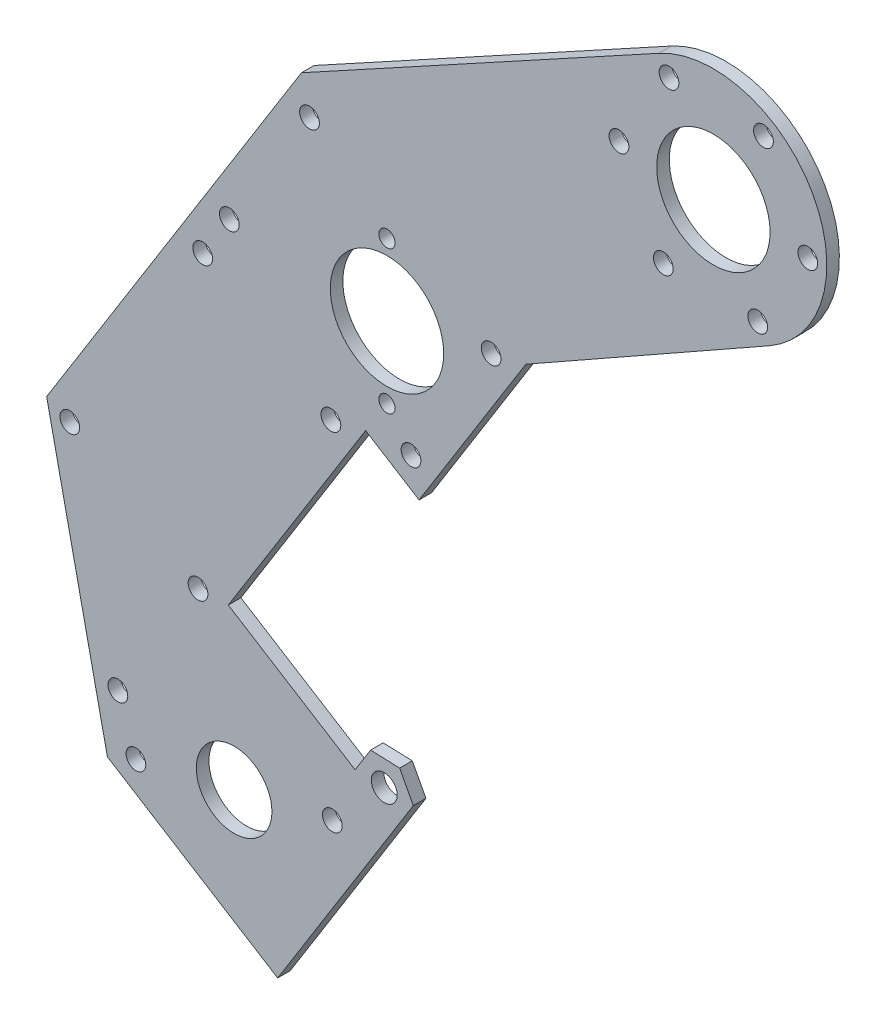
SolidWorks part; units mm, degrees
material "6061 Alloy"
ref_plane "Front Plane" through (0, 0, 0) normal (0, 0, 1) x (1, 0, 0)
ref_plane "Top Plane" through (0, 0, 0) normal (0, 1, 0) x (1, 0, 0)
ref_plane "Right Plane" through (0, 0, 0) normal (1, 0, 0) x (0, 0, -1)
sketch "Sketch1" plane through (0, 0, -14.1946) normal (0, 0, 1) x (1, 0, 0)
  line L0 (-11.4036, 461.0409) -> (18.8813, 509.5069)
  line L1 (-54.3079, 487.8505) -> (-69.6155, 558.824)
  line L2 (8.1111, 516.2368) -> (-23.8465, 536.2061)
  line L3 (18.8813, 509.5069) -> (22.7847, 515.7536)
  line L4 (-11.4036, 461.0409) -> (-54.3079, 487.8505)
  line L5 (-69.6155, 558.824) -> (-5.4017, 661.5875)
  line L6 (-23.8465, 536.2061) -> (10.7592, 591.5868)
  line L9 (12.0145, 522.4836) -> (8.1111, 516.2368)
  line L10 (51.1419, 626.2552) -> (112.462, 660.9373)
  line L11 (10.7592, 591.5868) -> (24.222, 583.1743)
  line L13 (24.222, 583.1743) -> (51.1419, 626.2552)
  line L16 (-5.4017, 661.5875) -> (84.678, 710.8773)
  line L17 (17.3996, 519.1186) -> (21.5031, 525.6857) construction
  line L18 (22.7847, 515.7536) -> (19.3423, 522.2277)
  line L19 (19.3423, 522.2277) -> (12.0145, 522.4836)
  circle A2 centre (16.1415, 618.1747) radius 14.2875
  circle A3 centre (-22.3737, 496.6228) radius 9.525
  circle A5 centre (98.3945, 685.8096) radius 14.2875
  arc A7 (112.462, 660.9373) -> (84.678, 710.8773) centre (98.3945, 685.8096) ccw
  circle A8 centre (16.1415, 618.1747) radius 127.508 construction
  circle A9 centre (15.4568, 516.0095) radius 6.35 construction
  point P12 (-22.3737, 496.6228)
  point P33 (98.3945, 685.8096)
  dimension "D1" = 120
extrude "Boss-Extrude1" add sketch "Sketch1" along normal blind 3.175
sketch "Sketch17" plane through (0, 0, -11.0196) normal (0, 0, 1) x (1, 0, 0)
  line L0 (-47.1227, 490.909) -> (-22.3737, 496.6228)
  line L1 (-22.3737, 496.6228) -> (2.3753, 502.3365)
  line L2 (16.1415, 618.1747) -> (37.6819, 604.7147) construction
  line L12 (24.222, 583.1743) -> (51.1419, 626.2552) construction
  line L13 (37.6819, 604.7147) -> (27.587, 588.5594) construction
  line L14 (27.587, 588.5594) -> (22.2019, 591.9244) construction
  line L15 (22.2019, 591.9244) -> (-28.9566, 623.8918) construction
  line L16 (-5.4017, 661.5875) -> (-69.6155, 558.824) construction
  line L17 (-28.9566, 623.8918) -> (-23.5715, 620.5268) construction
  line L18 (-23.5715, 620.5268) -> (-3.3816, 652.8374) construction
  line L19 (-3.3816, 652.8374) -> (42.3918, 624.2351) construction
  line L20 (10.7592, 591.5868) -> (5.3741, 594.9518) construction
  line L21 (5.3741, 594.9518) -> (-31.4748, 535.9811) construction
  line L22 (-31.4748, 535.9811) -> (-51.6648, 503.6705) construction
  line L23 (5.3741, 594.9518) -> (2.0091, 589.5667) construction
  line L24 (-31.4748, 535.9811) -> (-63.7855, 556.1711) construction
  line L25 (2.0091, 589.5667) -> (-30.3015, 609.7566) construction
  circle A0 centre (-22.3737, 496.6228) radius 25.4
  dimension "D1" = 50.8
hole_wizard "#10 Clearance Hole2" positions "Sketch20" profile "Sketch21" hole size "#10" standard "ANSI Inch" end condition through all
sketch "Sketch20" plane through (0, 0, -11.0196) normal (0, 0, 1) x (1, 0, 0)
  point P0 (2.3753, 502.3365)
  point P3 (-47.1227, 490.909)
  point P24 (-3.3816, 652.8374)
  point P27 (42.3918, 624.2351)
  point P30 (22.2019, 591.9244)
  point P33 (-23.5715, 620.5268)
  point P42 (-31.4748, 535.9811)
  point P45 (-63.7855, 556.1711)
  point P48 (-51.6648, 503.6705)
  point P54 (2.0091, 589.5667)
  point P57 (-30.3015, 609.7566)
sketch "Sketch21" plane through (2.3753, 502.3365, -11.0196) normal (1, 0, 0) x (0, -1, 0)
  line L0 (0, 0) -> (0, 3.175)
  line L1 (0, 3.175) -> (2.4892, 3.175)
  line L2 (2.4892, 3.175) -> (2.4892, 0)
  line L5 (2.4892, 0) -> (0, 0)
  line L11 (0, -6.35) -> (0, 107.95) construction
  dimension "Thru Hole Dia." = 4.9784
  dimension "Thru Hole Depth" = 3.175
sketch "Sketch22" plane through (0, 0, -11.0196) normal (0, 0, 1) x (1, 0, 0)
  line L0 (98.3945, 685.8096) -> (111.0132, 706.0038) construction
  line L2 (111.0132, 706.0038) -> (87.2152, 706.8348) construction
  line L3 (87.2152, 706.8348) -> (74.5965, 686.6407) construction
  line L4 (74.5965, 686.6407) -> (85.7758, 665.6155) construction
  line L5 (85.7758, 665.6155) -> (109.5738, 664.7845) construction
  line L6 (109.5738, 664.7845) -> (122.1925, 684.9786) construction
  line L7 (122.1925, 684.9786) -> (111.0132, 706.0038) construction
  circle A0 centre (98.3945, 685.8096) radius 23.8125 construction
hole_wizard "#10 Clearance Hole3" positions "Sketch23" profile "Sketch24" hole size "#10" standard "ANSI Inch" end condition through all
sketch "Sketch23" plane through (0, 0, -11.0196) normal (0, 0, 1) x (1, 0, 0)
  point P0 (111.0132, 706.0038)
  point P3 (122.1925, 684.9786)
  point P6 (109.5738, 664.7845)
  point P9 (85.7758, 665.6155)
  point P12 (74.5965, 686.6407)
  point P15 (87.2152, 706.8348)
sketch "Sketch24" plane through (111.0132, 706.0038, -11.0196) normal (1, 0, 0) x (0, -1, 0)
  line L0 (0, 0) -> (0, 3.175)
  line L1 (0, 3.175) -> (2.4892, 3.175)
  line L2 (2.4892, 3.175) -> (2.4892, 0)
  line L5 (2.4892, 0) -> (0, 0)
  line L11 (0, -6.35) -> (0, 107.95) construction
  dimension "Thru Hole Dia." = 4.9784
  dimension "Thru Hole Depth" = 3.175
hole_wizard "1/4 Clearance Hole1" positions "Sketch25" profile "Sketch26" hole size "1/4" standard "ANSI Inch" end condition through all
sketch "Sketch25" plane through (0, 0, -11.0196) normal (0, 0, 1) x (1, 0, 0)
  point P0 (15.4568, 516.0095)
sketch "Sketch26" plane through (15.4568, 516.0095, -11.0196) normal (1, 0, 0) x (0, -1, 0)
  line L0 (0, 0) -> (0, 3.175)
  line L1 (0, 3.175) -> (3.2639, 3.175)
  line L2 (3.2639, 3.175) -> (3.2639, 0)
  line L5 (3.2639, 0) -> (0, 0)
  line L11 (0, -6.35) -> (0, 107.95) construction
  dimension "Thru Hole Dia." = 6.5278
  dimension "Thru Hole Depth" = 3.175
hole_wizard "#20 (0.161) Diameter Hole1" positions "Sketch27" profile "Sketch28" hole size "#20" standard "ANSI Inch" end condition through all
sketch "Sketch27" plane through (0, 0, -14.1946) normal (0, 0, -1) x (-1, 0, 0)
  point P1 (-16.1415, 636.2087)
  point P4 (-16.1415, 600.1407)
sketch "Sketch28" plane through (16.1415, 636.2087, -14.1946) normal (1, 0, 0) x (0, 1, 0)
  line L0 (0, 0) -> (0, 3.175)
  line L1 (0, 3.175) -> (2.0447, 3.175)
  line L2 (2.0447, 3.175) -> (2.0447, 0)
  line L5 (2.0447, 0) -> (0, 0)
  line L11 (0, -6.35) -> (0, 107.95) construction
  dimension "Thru Hole Dia." = 4.0894
  dimension "Thru Hole Depth" = 3.175
